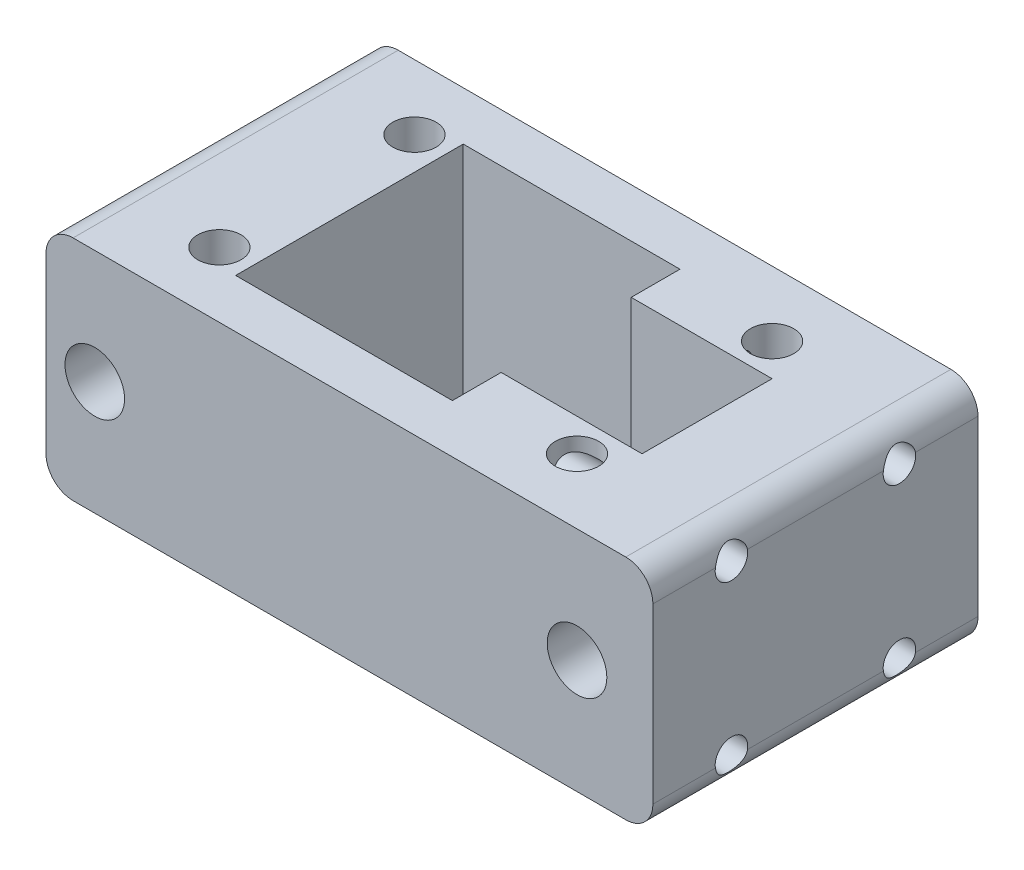
SolidWorks part; units mm, degrees
ref_plane "前基準面" through (0, 0, 0) normal (0, 0, 1) x (1, 0, 0)
ref_plane "上基準面" through (0, 0, 0) normal (0, 1, 0) x (1, 0, 0)
ref_plane "右基準面" through (0, 0, 0) normal (1, 0, 0) x (0, 0, -1)
sketch "草圖1" plane through (0, 0, 0) normal (0, 0, 1) x (1, 0, 0)
  line L0 (-59, 0) -> (53, 0) construction
  line L1 (-59, -21) -> (53, -21)
  line L2 (-59, -21) -> (-59, 21)
  line L3 (-59, 21) -> (53, 21)
  line L4 (53, -21) -> (53, 21)
  circle A0 centre (39, 0) radius 4
  circle A1 centre (-50, 0) radius 4
  circle A2 centre (-50, 0) radius 9.5 construction
  point P5 (-59, 0)
  dimension "D1" = 112
  dimension "D2" = 42
  dimension "D3" = 8
  dimension "D4" = 8
  dimension "D7" = 19
  dimension "D5" = 50
  dimension "D6" = 39
  dimension "D8" = 14
extrude "填料-伸長1" add sketch "草圖1" along normal blind 60
sketch "草圖2" plane through (0, 0, 0) normal (0, 0, -1) x (-1, 0, 0)
  line L0 (59, 0) -> (-53, 0) construction
  line L1 (59, 21) -> (59, -21) construction
  line L2 (-53, -21) -> (-53, 21) construction
  line L3 (4, -21) -> (4, 21) construction
  line L4 (59, -21) -> (-53, -21) construction
  line L5 (-53, 21) -> (59, 21) construction
  line L6 (25, -21) -> (25, 21) construction
  circle A0 centre (19.5, -15.5) radius 1.75
  circle A1 centre (-11.5, -15.5) radius 1.75
  circle A2 centre (-11.5, 15.5) radius 1.75
  circle A3 centre (19.5, 15.5) radius 1.75
  circle A4 centre (4, 0) radius 11.5
  dimension "D2" = 3.5
  dimension "D5" = 23
  dimension "D1" = 21
  dimension "D3" = 5.5
  dimension "D4" = 5.5
  dimension "D6" = 4
extrude "除料-伸長1" [suppressed] cut sketch "草圖2" against normal through all
sketch "草圖3" plane through (0, 21, 0) normal (0, 1, 0) x (1, 0, 0)
  line L0 (-59, -30) -> (53, -30) construction
  line L1 (-59, -60) -> (-59, 0) construction
  line L2 (53, -60) -> (53, 0) construction
  line L3 (-6, 0) -> (-6, -60) construction
  circle A0 centre (-39, -12) radius 4
  circle A1 centre (27, -12) radius 4
  circle A2 centre (27, -48) radius 4
  circle A3 centre (-39, -48) radius 4
  dimension "D1" = 8
  dimension "D2" = 33
  dimension "D3" = 18
  dimension "D8" = 6
extrude "除料-伸長2" cut sketch "草圖3" against normal through all
fillet "圓角1" radius 5 4 edges at (-59, -21, 30) (53, -21, 30) (53, 21, 30) (-59, 21, 30)
sketch "草圖4" [suppressed] plane through (0, 0, 60) normal (0, 0, 1) x (1, 0, 0)
  circle A0 centre (-4, 0) radius 11.5
extrude "填料-伸長2" [suppressed] add sketch "草圖4" against normal up to surface (5 mm away)
sketch "草圖5" [suppressed] plane through (0, 0, 60) normal (0, 0, 1) x (1, 0, 0)
  line L0 (-4, 21) -> (-4, -21) construction
  line L1 (50, 21) -> (-50, 21) construction
  line L2 (-50, -21) -> (50, -21) construction
  circle A0 centre (-19.5, 15.5) radius 3
  circle A1 centre (11.5, 15.5) radius 3
  circle A2 centre (11.5, -15.5) radius 3
  circle A3 centre (-19.5, -15.5) radius 3
  point P9 (-4, 0)
  point P19 (-4, 0)
  dimension "D1" = 6
  dimension "D2" = 4
  dimension "D3" = 4
extrude "除料-伸長3" [suppressed] cut sketch "草圖5" against normal blind 4
sketch "草圖6" plane through (0, 0, 60) normal (0, 0, 1) x (1, 0, 0)
  circle A0 centre (39, 0) radius 5.5
  dimension "D1" = 11
extrude "除料-伸長4" cut sketch "草圖6" against normal blind 10
sketch "草圖7" plane through (0, 0, 60) normal (0, 0, 1) x (1, 0, 0)
  circle A0 centre (-50, 0) radius 5.5
  dimension "D1" = 11
extrude "除料-伸長5" cut sketch "草圖7" against normal blind 42
sketch "草圖9" plane through (0, -21, 0) normal (0, -1, 0) x (1, 0, 0)
  line L0 (-59, 30) -> (53, 30) construction
  line L1 (-33, 51) -> (7, 51)
  line L2 (-33, 51) -> (-33, 9)
  line L3 (-33, 9) -> (7, 9)
  line L4 (7, 51) -> (7, 42)
  line L5 (-59, 0) -> (-59, 60) construction
  line L6 (53, 60) -> (53, 0) construction
  line L10 (7, 42) -> (33, 42)
  line L11 (33, 42) -> (33, 18)
  line L12 (33, 18) -> (7, 18)
  line L13 (7, 18) -> (7, 9)
  point P10 (33, 30)
  dimension "D1" = 42
  dimension "D2" = 40
  dimension "D4" = 26
  dimension "D5" = 24
  dimension "D9" = 26
extrude "除料-伸長7" cut sketch "草圖9" against normal through all
sketch "草圖10" plane through (53, 0, 0) normal (1, 0, 0) x (0, 0, -1)
  line L0 (0, -21) -> (-60, -21) construction
  line L1 (-51, -21) -> (-9, -21) construction
  line L2 (-51, -21) -> (-51, 21) construction
  line L3 (-51, 21) -> (-9, 21) construction
  line L4 (-9, -21) -> (-9, 21) construction
  line L5 (-30, 21) -> (-30, -21) construction
  line L6 (-60, 21) -> (0, 21) construction
  line L8 (-9, -21) -> (-9, 21) construction
  circle A0 centre (-45.5, -15.5) radius 1.75
  circle A1 centre (-45.5, 15.5) radius 1.75
  circle A2 centre (-14.5, 15.5) radius 1.75
  circle A3 centre (-14.5, -15.5) radius 1.75
  point P11 (-30, -21)
  dimension "D2" = 3.5
  dimension "D7" = 3.5
  dimension "D1" = 42
  dimension "D3" = 5.5
  dimension "D4" = 5.5
  dimension "D5" = 5.5
  dimension "D6" = 5.5
extrude "除料-伸長8" cut sketch "草圖10" against normal up to surface (46 mm away) up to face at (7, 0, 46.5)
sketch "草圖11" plane through (53, 0, 0) normal (1, 0, 0) x (0, 0, -1)
  circle A0 centre (-45.5, -15.5) radius 3
  circle A1 centre (-45.5, 15.5) radius 3
  circle A2 centre (-14.5, 15.5) radius 3
  circle A3 centre (-14.5, -15.5) radius 3
  dimension "D1" = 6
  dimension "D2" = 6
  dimension "D3" = 6
  dimension "D4" = 6
extrude "除料-伸長9" cut sketch "草圖11" against normal blind 40
